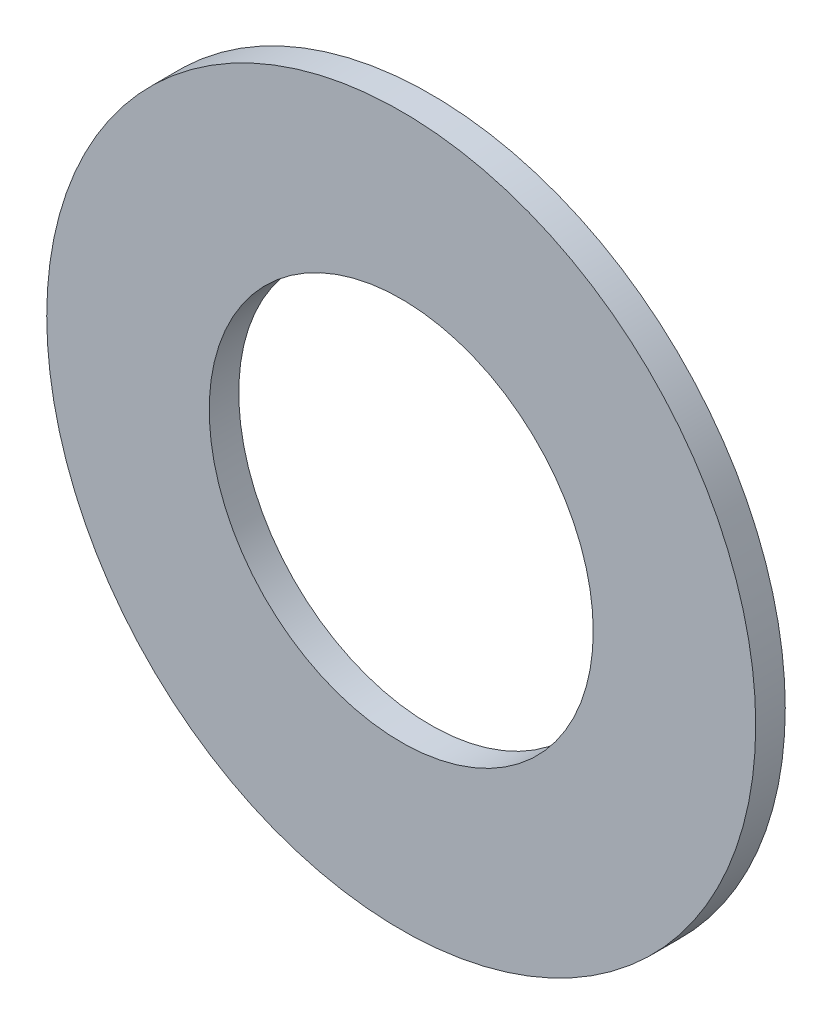
SolidWorks part; units mm, degrees
ref_plane "Plan de face" through (0, 0, 0) normal (0, 0, 1) x (1, 0, 0)
ref_plane "Plan de dessus" through (0, 0, 0) normal (0, 1, 0) x (1, 0, 0)
ref_plane "Plan de droite" through (0, 0, 0) normal (1, 0, 0) x (0, 0, -1)
sketch "Esquisse1" plane through (0, 0, 0) normal (0, 0, 1) x (1, 0, 0)
  circle A0 centre (0, 0) radius 24
  circle A1 centre (0, 0) radius 13
  dimension "D1" = 48
  dimension "D2" = 26
extrude "Boss.-Extru.1" add sketch "Esquisse1" along normal blind 2 contours A0 A1
